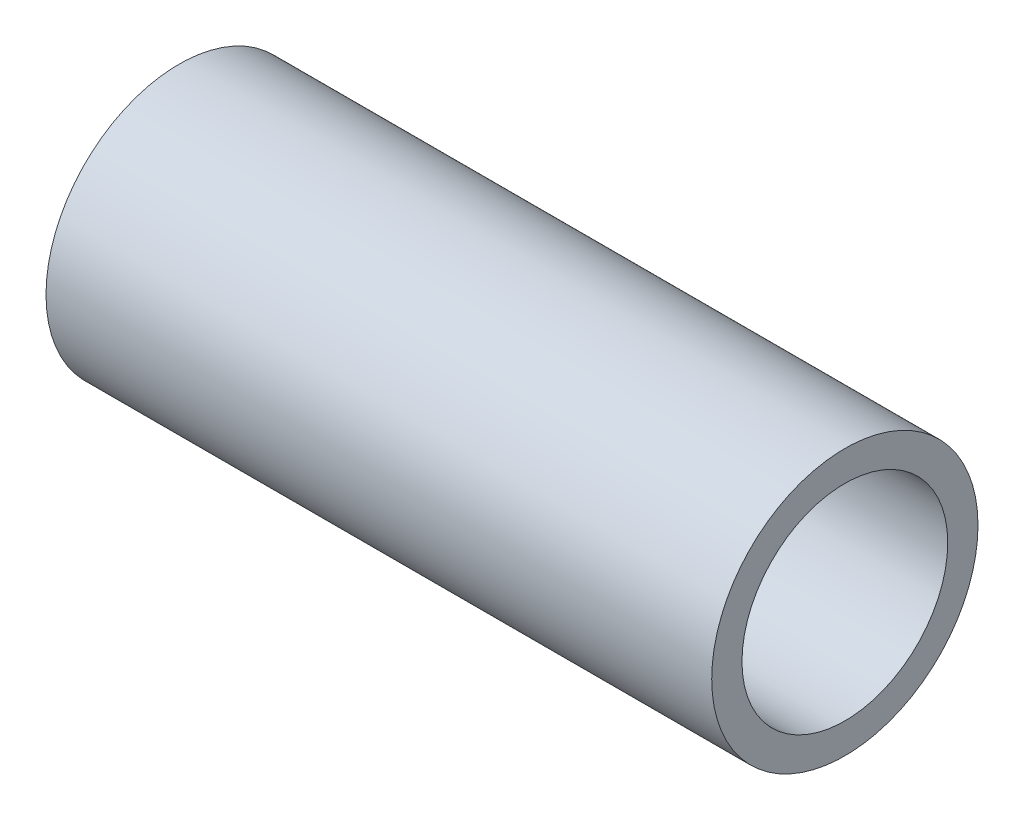
SolidWorks part; units mm, degrees
material "PVC 0.007 Plasticized"
ref_plane "Front Plane" through (0, 0, 0) normal (0, 0, 1) x (1, 0, 0)
ref_plane "Top Plane" through (0, 0, 0) normal (0, 1, 0) x (1, 0, 0)
ref_plane "Right Plane" through (0, 0, 0) normal (1, 0, 0) x (0, 0, -1)
sketch "Sketch1" plane through (0, 0, 0) normal (1, 0, 0) x (0, 0, -1)
  circle A0 centre (0, 0) radius 11
  circle A1 centre (0, 0) radius 8.5
  dimension "D1" = 2.5
extrude "Boss-Extrude1" add sketch "Sketch1" along normal blind 55
